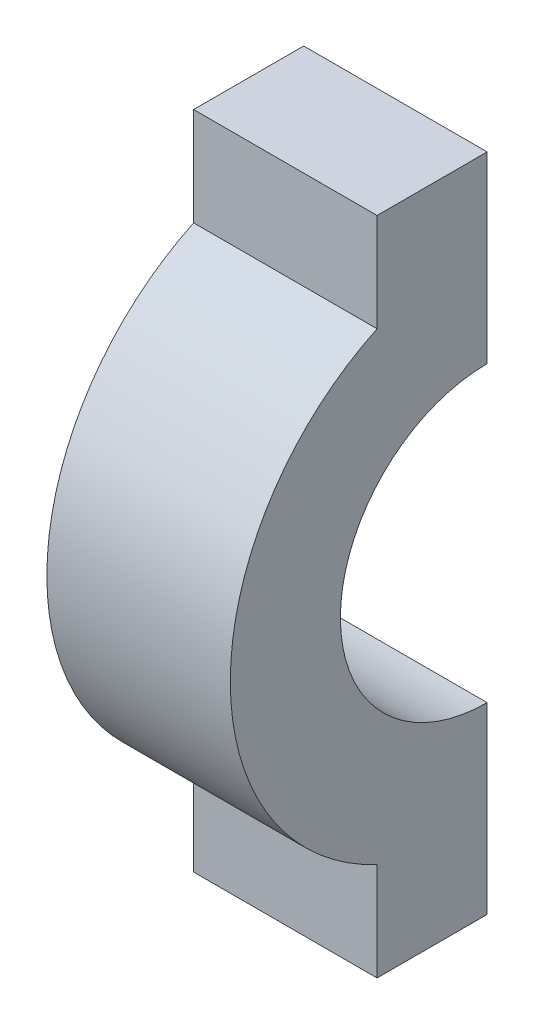
SolidWorks part; units mm, degrees
ref_plane "前视基准面" through (0, 0, 0) normal (0, 0, 1) x (1, 0, 0)
ref_plane "上视基准面" through (0, 0, 0) normal (0, 1, 0) x (1, 0, 0)
ref_plane "右视基准面" through (0, 0, 0) normal (1, 0, 0) x (0, 0, -1)
other "Configuration Table"
sketch "草图1" plane through (10, 0, 0) normal (1, 0, 0) x (0, 0, -1)
  line L0 (-18, 80) -> (-18, 90)
  line L1 (-18, 90) -> (-24, 90)
  line L2 (-24, 90) -> (-24, 84.6491)
  line L3 (-18, 64) -> (-18, 54)
  line L4 (-18, 54) -> (-24, 54)
  line L5 (-24, 54) -> (-24, 59.3509)
  arc A0 (-18, 80) -> (-18, 64) centre (-18, 72) ccw
  arc A1 (-24, 84.6491) -> (-24, 59.3509) centre (-18, 72) ccw
  arc A2 (-18, 64) -> (-18, 80) centre (-18, 72) ccw construction
  dimension "D1" = 6
  dimension "D2" = 6
extrude "凸台-拉伸1" add sketch "草图1" along normal mid plane 10
